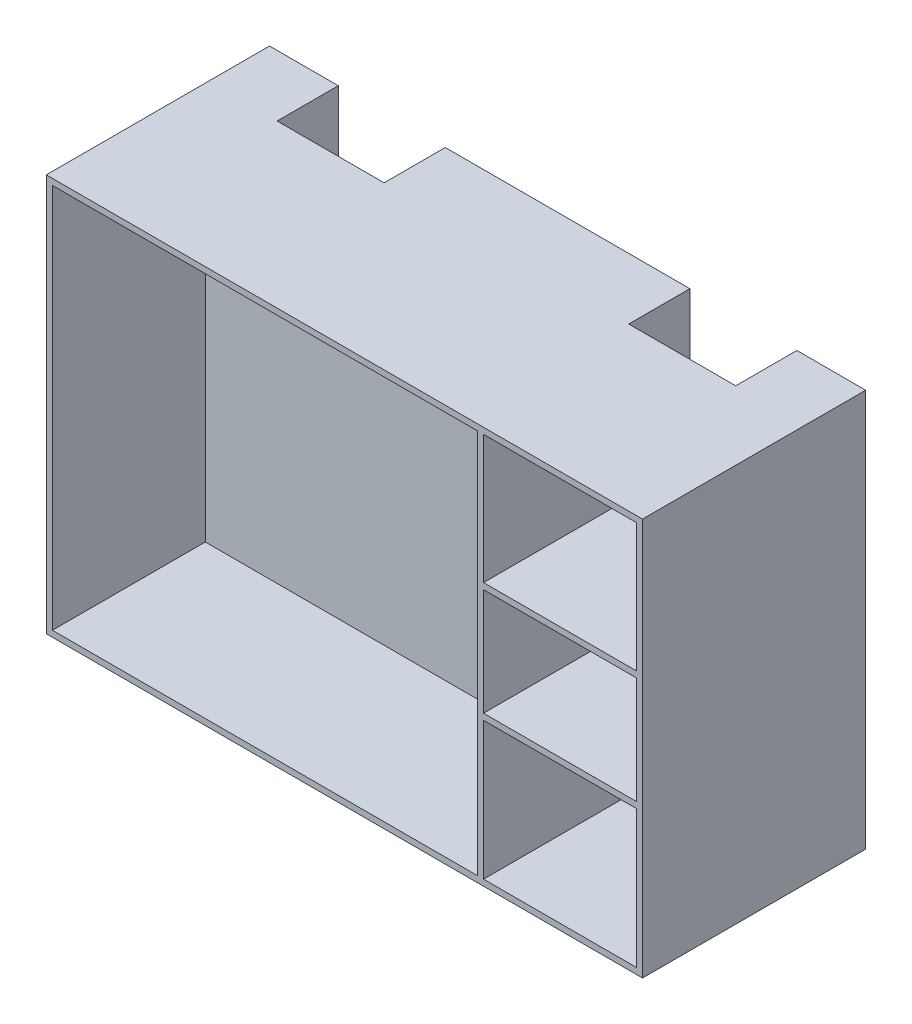
SolidWorks part; units mm, degrees
ref_plane "Ebene vorne" through (0, 0, 0) normal (0, 0, 1) x (1, 0, 0)
ref_plane "Ebene oben" through (0, 0, 0) normal (0, 1, 0) x (1, 0, 0)
ref_plane "Ebene rechts" through (0, 0, 0) normal (1, 0, 0) x (0, 0, -1)
ref_plane "Ebene1" through (0, 0, -3) normal (0, 0, -1) x (-1, 0, 0)
sketch "Skizze1" plane through (0, 0, -3) normal (0, 0, -1) x (-1, 0, 0)
  line L0 (69.193, -68.529) -> (69.193, 61.471)
  line L1 (69.193, 61.471) -> (-125.807, 61.471)
  line L2 (-125.807, 61.471) -> (-125.807, -68.529)
  line L3 (-125.807, -68.529) -> (69.193, -68.529)
extrude "Aufsatz-Linear austragen1" add sketch "Skizze1" against normal blind 53
sketch "Skizze2" plane through (0, 0, 50) normal (0, 0, 1) x (1, 0, 0)
  line L0 (71.807, -66.529) -> (71.807, 59.471)
  line L1 (71.807, 59.471) -> (-67.193, 59.471)
  line L2 (-67.193, 59.471) -> (-67.193, -66.529)
  line L3 (-67.193, -66.529) -> (71.807, -66.529)
extrude "Schnitt-Linear austragen1" cut sketch "Skizze2" against normal blind 50
sketch "Skizze3" plane through (0, 0, 50) normal (0, 0, 1) x (1, 0, 0)
  line L0 (73.807, 17.471) -> (123.807, 17.471)
  line L1 (123.807, 17.471) -> (123.807, 59.471)
  line L2 (123.807, 59.471) -> (73.807, 59.471)
  line L3 (73.807, 59.471) -> (73.807, 17.471)
extrude "Schnitt-Linear austragen2" cut sketch "Skizze3" against normal blind 50
sketch "Skizze4" plane through (0, 0, 50) normal (0, 0, 1) x (1, 0, 0)
  line L0 (73.807, -21.529) -> (73.807, -66.529)
  line L1 (73.807, -66.529) -> (123.807, -66.529)
  line L2 (123.807, -66.529) -> (123.807, -21.529)
  line L3 (123.807, -21.529) -> (73.807, -21.529)
extrude "Schnitt-Linear austragen3" cut sketch "Skizze4" against normal blind 50
sketch "Skizze5" plane through (0, 0, 50) normal (0, 0, 1) x (1, 0, 0)
  line L0 (73.807, 15.471) -> (73.807, -19.529)
  line L1 (73.807, -19.529) -> (123.807, -19.529)
  line L2 (123.807, -19.529) -> (123.807, 15.471)
  line L3 (123.807, 15.471) -> (73.807, 15.471)
extrude "Schnitt-Linear austragen4" cut sketch "Skizze5" against normal blind 50
sketch "Skizze6" plane through (0, 0, -3) normal (0, 0, -1) x (-1, 0, 0)
  line L1 (-125.807, 61.471) -> (69.193, 61.471)
  line L2 (-125.807, 61.471) -> (-125.807, -68.529)
  line L3 (-125.807, -68.529) -> (69.193, -68.529)
  line L4 (69.193, 61.471) -> (69.193, -68.529)
extrude "Aufsatz-Linear austragen2" add sketch "Skizze6" along normal blind 20
sketch "Skizze7" plane through (0, 0, -23) normal (0, 0, -1) x (-1, 0, 0)
  line L0 (69.193, 61.471) -> (-125.807, 61.471) construction
  line L1 (-103.307, 61.471) -> (-68.307, 61.471)
  line L2 (-103.307, 61.471) -> (-103.307, -68.529)
  line L3 (-103.307, -68.529) -> (-68.307, -68.529)
  line L4 (-68.307, 61.471) -> (-68.307, -68.529)
  line L5 (-125.807, -68.529) -> (69.193, -68.529) construction
  line L6 (-125.807, 61.471) -> (-125.807, -68.529) construction
  line L7 (11.693, 61.471) -> (46.693, 61.471)
  line L8 (11.693, 61.471) -> (11.693, -68.529)
  line L9 (11.693, -68.529) -> (46.693, -68.529)
  line L10 (46.693, 61.471) -> (46.693, -68.529)
  line L11 (69.193, -68.529) -> (69.193, 61.471) construction
  dimension "D1" = 35
  dimension "D2" = 35
  dimension "D3" = 80
  dimension "D4" = 22.5
  dimension "D5" = 195
  dimension "D6" = 22.5
extrude "Schnitt-Linear austragen5" cut sketch "Skizze7" against normal blind 20
